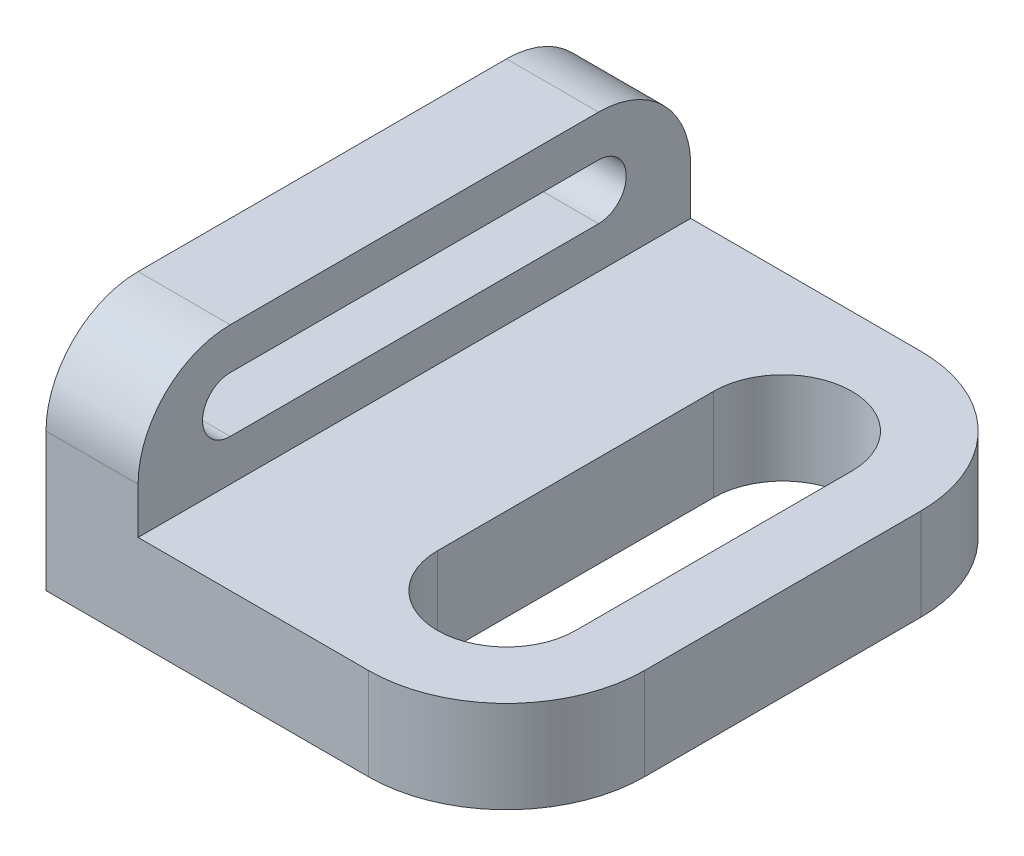
SolidWorks part; units mm, degrees
ref_plane "Front Plane" through (0, 0, 0) normal (0, 0, 1) x (1, 0, 0)
ref_plane "Top Plane" through (0, 0, 0) normal (0, 1, 0) x (1, 0, 0)
ref_plane "Right Plane" through (0, 0, 0) normal (1, 0, 0) x (0, 0, -1)
sketch "Sketch1" plane through (0, 0, 0) normal (0, 1, 0) x (1, 0, 0)
  line L0 (20, 30) -> (20, -30) construction
  line L1 (-50, 60) -> (20, 60)
  line L2 (-50, 60) -> (-50, -60)
  line L3 (-50, -60) -> (20, -60)
  line L4 (50, 30) -> (50, -30)
  line L5 (-50, 60) -> (50, -60) construction
  line L6 (-50, -60) -> (50, 60) construction
  line L11 (35, 30) -> (35, -30)
  line L14 (5, 30) -> (5, -30)
  line L15 (-50, 0) -> (50, 0) construction
  arc A0 (50, -30) -> (20, -60) centre (20, -30) cw
  arc A1 (50, 30) -> (20, 60) centre (20, 30) ccw
  arc A4 (35, 30) -> (5, 30) centre (20, 30) ccw
  arc A5 (5, -30) -> (35, -30) centre (20, -30) ccw
  point P0 (0, 0)
  point P14 (20, 0)
  dimension "D3" = 30
  dimension "D5" = 15
  dimension "D1" = 100
  dimension "D2" = 120
  dimension "D4" = 60
extrude "Boss-Extrude1" add sketch "Sketch1" along normal blind 20
sketch "Sketch2" plane through (0, 20, 0) normal (0, 1, 0) x (1, 0, 0)
  line L0 (-40, 60) -> (-40, -60) construction
  line L1 (20, 60) -> (-50, 60) construction
  line L2 (-50, -60) -> (20, -60) construction
  line L4 (-30, -60) -> (-50, -60)
  line L5 (-30, -60) -> (-30, 60)
  line L6 (-30, 60) -> (-50, 60)
  line L7 (-50, -60) -> (-50, 60)
  line L8 (-30, -60) -> (-50, 60) construction
  line L9 (-30, 60) -> (-50, -60) construction
  point P6 (-40, 0)
  dimension "D1" = 10
  dimension "D2" = 20
extrude "Boss-Extrude2" add sketch "Sketch2" along normal blind 30
sketch "Sketch3" plane through (-30, 0, 0) normal (1, 0, 0) x (0, 0, -1)
  line L0 (0, 50) -> (0, 20) construction
  line L1 (-60, 50) -> (60, 50) construction
  line L2 (-30, 20) -> (30, 20) construction
  line L3 (-40, 50) -> (-60, 50)
  line L4 (40, 50) -> (-40, 50)
  line L8 (60, 50) -> (-60, 20) construction
  line L9 (60, 20) -> (-60, 50) construction
  line L10 (-60, 50) -> (-60, 30)
  line L11 (40, 50) -> (60, 50)
  line L12 (60, 50) -> (60, 30)
  line L13 (-40, 35) -> (40, 35) construction
  line L14 (-40, 35) -> (40, 35) construction
  line L15 (-40, 41) -> (40, 41)
  line L16 (-40, 29) -> (40, 29)
  arc A0 (60, 30) -> (40, 50) centre (40, 30) ccw
  arc A1 (-40, 50) -> (-60, 30) centre (-40, 30) ccw
  arc A2 (-40, 41) -> (-40, 29) centre (-40, 35) ccw
  arc A3 (40, 29) -> (40, 41) centre (40, 35) ccw
  point P6 (0, 35)
  point P20 (0, 35)
  dimension "D1" = 20
  dimension "D3" = 6
  dimension "D2" = 80
extrude "Cut-Extrude1" cut sketch "Sketch3" against normal up to surface (20 mm away) contours L3 L10 A1 | L16 A3 L15 A2 | L11 L12 A0 up to face at (-50, 25, 0)
